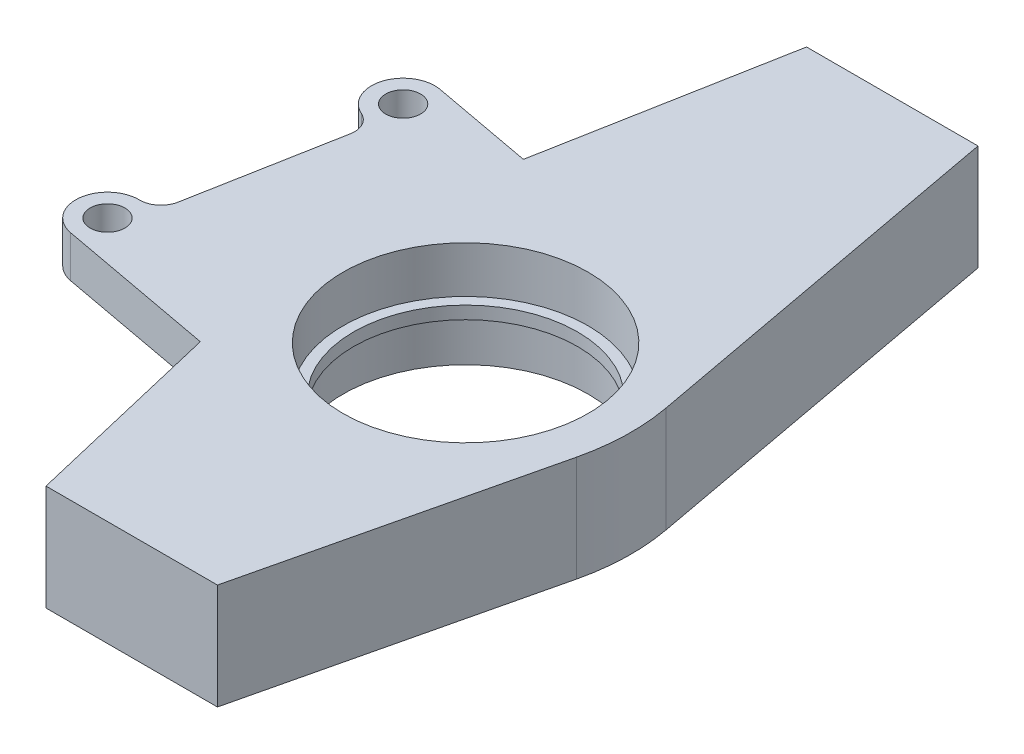
SolidWorks part; units mm, degrees
ref_plane "Front Plane" through (0, 0, 0) normal (0, 0, 1) x (1, 0, 0)
ref_plane "Top Plane" through (0, 0, 0) normal (0, 1, 0) x (1, 0, 0)
ref_plane "Right Plane" through (0, 0, 0) normal (1, 0, 0) x (0, 0, -1)
sketch "Sketch1" plane through (0, 0, 0) normal (0, 1, 0) x (1, 0, 0)
  line L0 (-20.6135, -80.2794) -> (20.6135, -80.2794)
  line L1 (39.624, 0) -> (20.6135, 102.6006)
  line L2 (20.6135, 102.6006) -> (-20.6135, 102.6006)
  line L4 (20.6135, 102.6006) -> (20.6135, -80.2794) construction
  line L5 (20.6135, -80.2794) -> (39.624, 0)
  line L9 (0, 0) -> (-120.65, 0) construction
  line L10 (0, 0) -> (120.65, 0) construction
  line L11 (0, 0) -> (0, 29.464) construction
  line L12 (-20.6135, -80.2794) -> (-39.624, 0)
  line L13 (-39.624, 0) -> (-20.6135, 102.6006)
  circle A0 centre (0, 0) radius 29.464
  circle A2 centre (0, 0) radius 120.65
  point P2 (0, -80.2794)
  point P10 (0, -29.464)
  point P11 (29.464, 0)
  point P16 (-29.464, 0)
  point P17 (0, 102.6006)
  dimension "D2" = 58.928
  dimension "D3" = 10.16
  dimension "D5" = 182.88
  dimension "D1" = 241.3
extrude "Base" add sketch "Sketch1" along normal blind 25.4
sketch "Sketch2" plane through (0, 0, 0) normal (0, 1, 0) x (1, 0, 0)
  line L0 (20.6135, 102.6006) -> (21.3194, 98.7906)
  line L1 (39.624, 0) -> (20.6135, 102.6006) construction
  line L2 (21.3194, 98.7906) -> (-12.4065, 98.7906)
  line L3 (-12.4065, 98.7906) -> (-12.4065, 102.6006)
  line L4 (20.6135, 102.6006) -> (-20.6135, 102.6006) construction
  line L5 (-12.4065, 102.6006) -> (20.6135, 102.6006)
  line L6 (-12.4065, -76.4694) -> (21.5157, -76.4694)
  line L7 (21.5157, -76.4694) -> (20.6135, -80.2794)
  line L8 (-20.6135, -80.2794) -> (20.6135, -80.2794) construction
  line L9 (20.6135, -80.2794) -> (-12.4065, -80.2794)
  line L10 (-12.4065, -80.2794) -> (-12.4065, -76.4694)
  line L11 (-12.4065, 102.6006) -> (-12.4065, -80.2794) construction
  line L12 (20.6135, -80.2794) -> (39.624, 0) construction
  line L13 (-12.4065, 79.7406) -> (-12.4065, 75.9306)
  line L14 (-12.4065, 75.9306) -> (25.5551, 75.9306)
  line L15 (25.5551, 75.9306) -> (24.8491, 79.7406)
  line L16 (24.8491, 79.7406) -> (-12.4065, 79.7406)
  line L18 (-12.4065, -53.6094) -> (26.929, -53.6094)
  line L19 (-12.4065, -53.6094) -> (-12.4065, -57.4194)
  line L20 (-12.4065, -57.4194) -> (26.0268, -57.4194)
  line L21 (26.929, -53.6094) -> (26.0268, -57.4194)
  dimension "D1" = 33.02
  dimension "D2" = 3.81
  dimension "D3" = 3.81
  dimension "D4" = 19.05
  dimension "D5" = 3.81
  dimension "D6" = 3.81
  dimension "D7" = 19.05
fillet "Fillet2" radius 50.8 1 edges at (39.624, 12.7, 0)
ref_plane "Plane1" through (0, 1, 0) normal (0, -1, 0) x (-1, 0, 0)
sketch "Sketch3" plane through (0, 25.4, 0) normal (0, -1, 0) x (-1, 0, 0)
  line L0 (31.2571, 45.1566) -> (55.8441, 49.7122)
  line L1 (20.6135, -80.2794) -> (39.624, 0) construction
  line L2 (32.1275, -31.657) -> (70.4299, -24.56)
  line L3 (57.3868, 29.685) -> (63.868, -5.2943)
  line L5 (39.624, 0) -> (20.6135, 102.6006) construction
  circle A0 centre (0, 0) radius 71.12
  circle A1 centre (57.2324, 42.2198) radius 4.191
  circle A2 centre (69.0417, -17.0676) radius 4.191
  arc A3 (60.322, 35.2542) -> (55.8441, 49.7122) centre (57.2324, 42.2198) ccw
  arc A4 (70.4299, -24.56) -> (68.9345, -9.4483) centre (69.0417, -17.0676) ccw
  arc A5 (63.868, -5.2943) -> (68.9345, -9.4483) centre (68.863, -4.3688) ccw
  arc A6 (57.3868, 29.685) -> (60.322, 35.2542) centre (62.3818, 30.6106) cw
  point P11 (0, 0)
  point P12 (32.1275, -31.657)
  point P19 (25.8369, 46.5582)
  point P22 (45.9289, -26.2721)
  dimension "D1" = 60.452
  dimension "D2" = 142.24
  dimension "D3" = 8.382
  dimension "D4" = 8.382
  dimension "D5" = 15.24
  dimension "D6" = 15.24
  dimension "D7" = 5.08
extrude "Boss-Extrude3" add sketch "Sketch3" along normal blind 10
ref_plane "midplane" through (0, 12.7, 0) normal (0, 1, 0) x (1, 0, 0)
sketch "Sketch8" plane through (0, 12.7, 0) normal (0, 1, 0) x (1, 0, 0)
  circle A2 centre (0, 0) radius 29.464 construction
  circle A3 centre (0, 0) radius 29.464
  circle A5 centre (0, 0) radius 26.924
  dimension "D1" = 2.54
extrude "mid-feature bearing" add sketch "Sketch8" along normal blind 1.524 and the other way blind 1.524
mirror "Mirror2" [suppressed]
delete or keep bodies "Body-Delete/Keep 1" [suppressed] type delete bodies bodies 108
